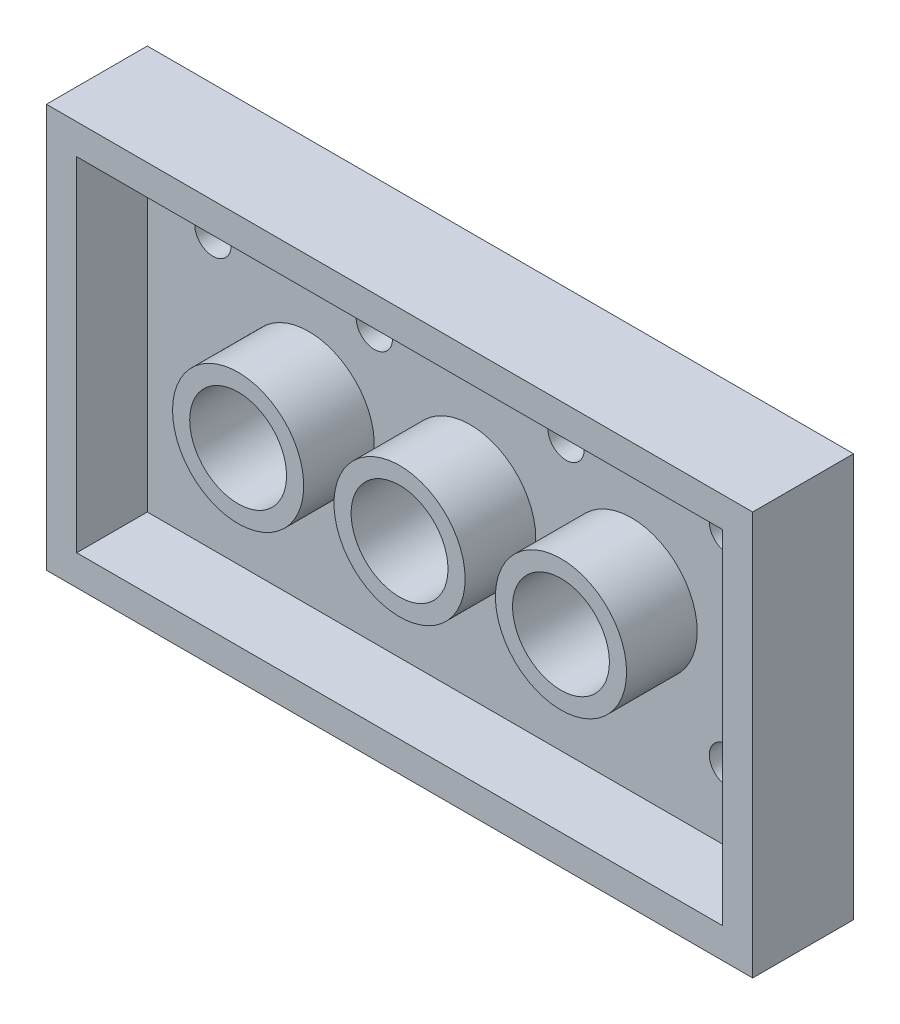
SolidWorks part; units mm, degrees
material "ABS"
ref_plane "Front Plane" through (0, 0, 0) normal (0, 0, 1) x (1, 0, 0)
ref_plane "Top Plane" through (0, 0, 0) normal (0, 1, 0) x (1, 0, 0)
ref_plane "Right Plane" through (0, 0, 0) normal (1, 0, 0) x (0, 0, -1)
sketch "Sketch1" plane through (0, 0, 0) normal (0, 0, 1) x (1, 0, 0)
  line L1 (-17.5, 10) -> (17.5, 10)
  line L2 (-17.5, 10) -> (-17.5, -10)
  line L3 (-17.5, -10) -> (17.5, -10)
  line L4 (17.5, 10) -> (17.5, -10)
  line L5 (-17.5, 10) -> (17.5, -10) construction
  line L6 (-17.5, -10) -> (17.5, 10) construction
  line L7 (-16, 8.5) -> (16, 8.5)
  line L8 (-16, 8.5) -> (-16, -8.5)
  line L9 (-16, -8.5) -> (16, -8.5)
  line L10 (16, 8.5) -> (16, -8.5)
  line L11 (-16, 8.5) -> (16, -8.5) construction
  line L12 (-16, -8.5) -> (16, 8.5) construction
  point P0 (0, 0)
  point P6 (0, 0)
  dimension "D1" = 35
  dimension "D2" = 20
  dimension "D3" = 1.5
  dimension "D4" = 1.5
extrude "Boss-Extrude1" add sketch "Sketch1" along normal blind 5
sketch "Sketch2" plane through (0, 0, 0) normal (0, 0, 1) x (1, 0, 0)
  line L0 (16, -8.5) -> (16, 8.5) construction
  line L1 (-16, -8.5) -> (16, -8.5) construction
  line L2 (-16, 8.5) -> (-16, -8.5) construction
  line L3 (16, 8.5) -> (-16, 8.5) construction
  line L4 (16, -8.5) -> (16, 8.5)
  line L5 (-16, -8.5) -> (16, -8.5)
  line L6 (-16, 8.5) -> (-16, -8.5)
  line L7 (16, 8.5) -> (-16, 8.5)
extrude "Boss-Extrude2" add sketch "Sketch2" along normal blind 1.5
sketch "Sketch3" plane through (0, 0, 0) normal (0, 0, -1) x (-1, 0, 0)
  line L3 (-17.5, 0) -> (17.5, 0)
  line L4 (17.5, 10) -> (17.5, -10) construction
  line L5 (0, 10) -> (0, -10)
  line L6 (17.5, -10) -> (-17.5, -10) construction
  line L9 (0, -5) -> (17.5, -5)
  line L10 (12.75, 0) -> (12.75, -10)
  line L13 (4.75, 0) -> (4.75, -10)
  circle A8 centre (12.75, -5) radius 2.4
  circle A9 centre (4.75, -5) radius 2.4
  circle A10 centre (12.75, 5) radius 2.4
  circle A11 centre (4.75, 5) radius 2.4
  circle A12 centre (-12.75, -5) radius 2.4
  circle A13 centre (-12.75, 5) radius 2.4
  circle A14 centre (-4.75, 5) radius 2.4
  circle A15 centre (-4.75, -5) radius 2.4
  point P5 (0, 0)
  point P10 (0, 0)
  dimension "D4" = 4.8
  dimension "D1" = 8
  dimension "D2" = 5
  dimension "D3" = 4.75
extrude "Boss-Extrude3" add sketch "Sketch3" along normal blind 1.8 contours L9 A8 L10 | L10 A8 L9 | L9 A8 L10 | L10 A8 L9 | A10 | A14 | A15 | A12 | A13 | A9 | A11
sketch "Sketch6" plane through (0, 0, 1.5) normal (0, 0, 1) x (1, 0, 0)
  line L0 (-9.6119, 0) -> (10.3614, 0) construction
  line L1 (0, 5.1318) -> (0, -5.0015) construction
  circle A0 centre (0, 0) radius 3.25
  circle A2 centre (8, 0) radius 3.25
  circle A3 centre (0, 0) radius 2.4
  circle A4 centre (8, 0) radius 2.4
  circle A5 centre (-8, 0) radius 2.4
  circle A6 centre (-8, 0) radius 3.25
  dimension "D1" = 4.8
  dimension "D2" = 6.5
  dimension "D3" = 8
extrude "Boss-Extrude4" add sketch "Sketch6" along normal blind 3.5
sketch "Sketch7" plane through (0, 0, 1.5) normal (0, 0, 1) x (1, 0, 0)
  line L0 (0, 8.5) -> (0, -8.5)
  line L1 (16, 8.5) -> (-16, 8.5) construction
  line L2 (-16, -8.5) -> (16, -8.5) construction
  line L3 (0, 0) -> (16, 0)
  line L4 (16, -8.5) -> (16, 8.5) construction
  line L5 (0, -5) -> (16, -5)
  line L7 (4.75, 0) -> (4.75, -8.5)
  line L8 (-16, -8.5) -> (16, -8.5) construction
  line L9 (12.75, 0) -> (12.75, -8.5)
  line L10 (17.5, -10) -> (17.5, 10) construction
  line L11 (16, -8.5) -> (16, 8.5) construction
  circle A0 centre (4.75, -5) radius 0.9
  circle A1 centre (12.75, -5) radius 0.9
  circle A2 centre (12.75, 5) radius 0.9
  circle A3 centre (4.75, 5) radius 0.9
  circle A4 centre (-4.75, 5) radius 0.9
  circle A5 centre (-12.75, 5) radius 0.9
  circle A6 centre (-12.75, -5) radius 0.9
  circle A7 centre (-4.75, -5) radius 0.9
  point P25 (12.75, -5)
  dimension "D1" = 8
  dimension "D4" = 1.8
  dimension "D2" = 4.75
  dimension "D3" = 5
extrude "Cut-Extrude2" cut sketch "Sketch7" against normal blind 1.8 contours A2 | A5 | A6 | A7 | A1 | A3 | A4 | A0
equation "\"B\" = 35"
equation "\"D1@Sketch1\"=\"B\""
equation "\"A\" = 20"
equation "\"D2@Sketch1\"=\"A\""
equation "\"C\"= 10 / 2"
equation "\"D1@Boss-Extrude1\"=\"C\""
equation "\"D2@Sketch3\"=\"A\"/4"
equation "\"D3@Sketch3\"=(\"B\"/2 - 8)/2"
equation "\"D2@Sketch7\"=(\"B\"/2-8)/2"
equation "\"D3@Sketch7\"=\"A\"/4"
equation "\"D1@Boss-Extrude4\"=\"C\"-1.5"
